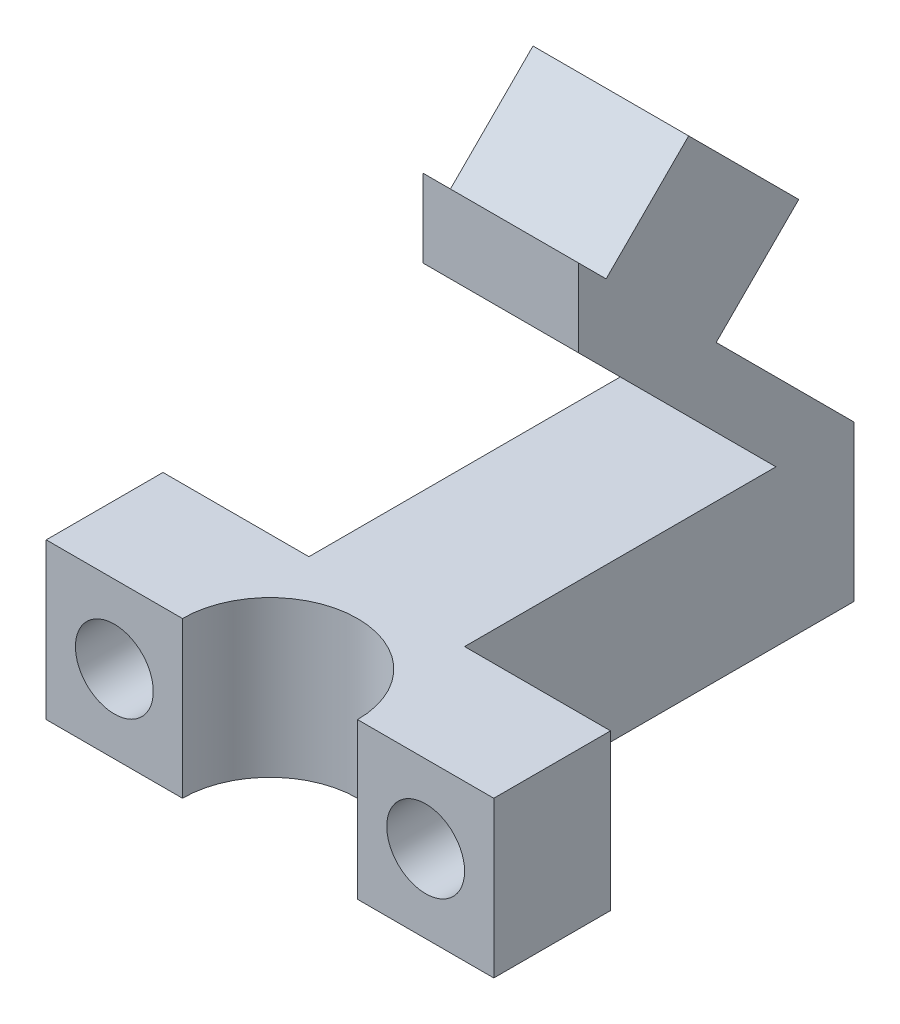
SolidWorks part; units mm, degrees
ref_plane "Front Plane" through (0, 0, 0) normal (0, 0, 1) x (1, 0, 0)
ref_plane "Top Plane" through (0, 0, 0) normal (0, 1, 0) x (1, 0, 0)
ref_plane "Right Plane" through (0, 0, 0) normal (1, 0, 0) x (0, 0, -1)
sketch "Sketch2" plane through (0, 0, 0) normal (0, 0, 1) x (1, 0, 0)
  line L1 (-59.6296, 43.5053) -> (55.3704, 43.5053)
  line L2 (-59.6296, 43.5053) -> (-59.6296, 3.5053)
  line L3 (-59.6296, 3.5053) -> (55.3704, 3.5053)
  line L4 (55.3704, 43.5053) -> (55.3704, 3.5053)
  dimension "D1" = 115
  dimension "D2" = 40
extrude "Boss-Extrude1" add sketch "Sketch2" along normal blind 60
sketch "Sketch3" plane through (0, 43.5053, 0) normal (0, 1, 0) x (1, 0, 0)
  line L0 (-59.6296, -60) -> (-59.6296, 0) construction
  line L1 (-59.6296, -30) -> (-24.6296, -30)
  line L2 (-59.6296, -30) -> (-59.6296, -60)
  line L3 (-59.6296, -60) -> (55.3704, -60)
  line L4 (55.3704, -30) -> (55.3704, -60)
  line L5 (20.3704, -30) -> (55.3704, -30)
  arc A0 (20.3704, -30) -> (-24.6296, -30) centre (-2.1296, -30) ccw
  dimension "D1" = 35
  dimension "D3" = 22.5
  dimension "D2" = 35
  dimension "D4" = 45
extrude "Cut-Extrude1" cut sketch "Sketch3" against normal blind 60
sketch "Sketch4" plane through (0, 0, 30) normal (0, 0, 1) x (1, 0, 0)
  line L0 (-24.6296, 3.5053) -> (-59.6296, 3.5053) construction
  line L1 (-59.6296, 3.5053) -> (-59.6296, 43.5053) construction
  line L2 (55.3704, 3.5053) -> (55.3704, 43.5053) construction
  line L3 (55.3704, 3.5053) -> (20.3704, 3.5053) construction
  circle A0 centre (-42.1296, 23.5053) radius 10
  circle A1 centre (37.8704, 23.5053) radius 10
  dimension "D1" = 20
  dimension "D3" = 17.5
  dimension "D2" = 17.5
  dimension "D4" = 20
  dimension "D5" = 80
extrude "Cut-Extrude2" cut sketch "Sketch4" against normal blind 60
sketch "Sketch5" plane through (0, 0, 0) normal (0, 0, -1) x (-1, 0, 0)
  line L0 (-55.3704, 43.5053) -> (59.6296, 43.5053) construction
  line L1 (-17.8704, 43.5053) -> (22.1296, 43.5053)
  line L2 (-17.8704, 43.5053) -> (-17.8704, 3.5053)
  line L3 (-17.8704, 3.5053) -> (22.1296, 3.5053)
  line L4 (22.1296, 43.5053) -> (22.1296, 3.5053)
  line L5 (59.6296, 3.5053) -> (-55.3704, 3.5053) construction
  circle A0 centre (-37.8704, 23.5053) radius 10 construction
  circle A1 centre (42.1296, 23.5053) radius 10 construction
  dimension "D1" = 20
  dimension "D2" = 20
  dimension "D3" = 40
extrude "Boss-Extrude2" add sketch "Sketch5" along normal blind 100
sketch "Sketch9" plane through (0, 43.5053, 0) normal (0, 1, 0) x (1, 0, 0)
  line L1 (17.8704, 100) -> (-22.1296, 100)
  line L2 (17.8704, 100) -> (17.8704, 0)
  line L3 (17.8704, 0) -> (-22.1296, 0)
  line L4 (-22.1296, 100) -> (-22.1296, 0)
extrude "Boss-Extrude4" add sketch "Sketch9" along normal blind 100
sketch "Sketch10" plane through (17.8704, 0, 0) normal (1, 0, 0) x (0, 0, -1)
  line L0 (0, 43.5053) -> (171.3693, 43.5053) construction
  line L1 (100, 43.5053) -> (29.2893, 114.216)
  line L2 (100, 143.5053) -> (100, 3.5053) construction
  line L3 (29.2893, 114.216) -> (29.2893, 94.216)
  line L4 (29.2893, 94.216) -> (80, 43.5053)
  line L5 (80, 43.5053) -> (0, 43.5053)
  line L6 (0, 43.5053) -> (0, 143.5053)
  line L7 (0, 143.5053) -> (100, 143.5053)
  line L8 (100, 143.5053) -> (100, 43.5053)
  dimension "D1" = 100
  dimension "D2" = 20
extrude "Cut-Extrude10" cut sketch "Sketch10" against normal blind 100
sketch "Sketch12" plane through (0, 71.7526, -71.7526) normal (0, 0.7071, -0.7071) x (1, 0, 0)
  line L0 (17.8704, -60.0522) -> (17.8704, 39.9478) construction
  line L1 (17.8704, -50.0522) -> (-22.1296, -50.0522)
  line L2 (17.8704, -50.0522) -> (17.8704, -10.0522)
  line L3 (17.8704, -10.0522) -> (-22.1296, -10.0522)
  line L4 (-22.1296, -50.0522) -> (-22.1296, -10.0522)
  line L5 (-22.1296, -60.0522) -> (-22.1296, 39.9478) construction
  dimension "D1" = 40
  dimension "D2" = 10
extrude "Boss-Extrude6" add sketch "Sketch12" along normal blind 30
